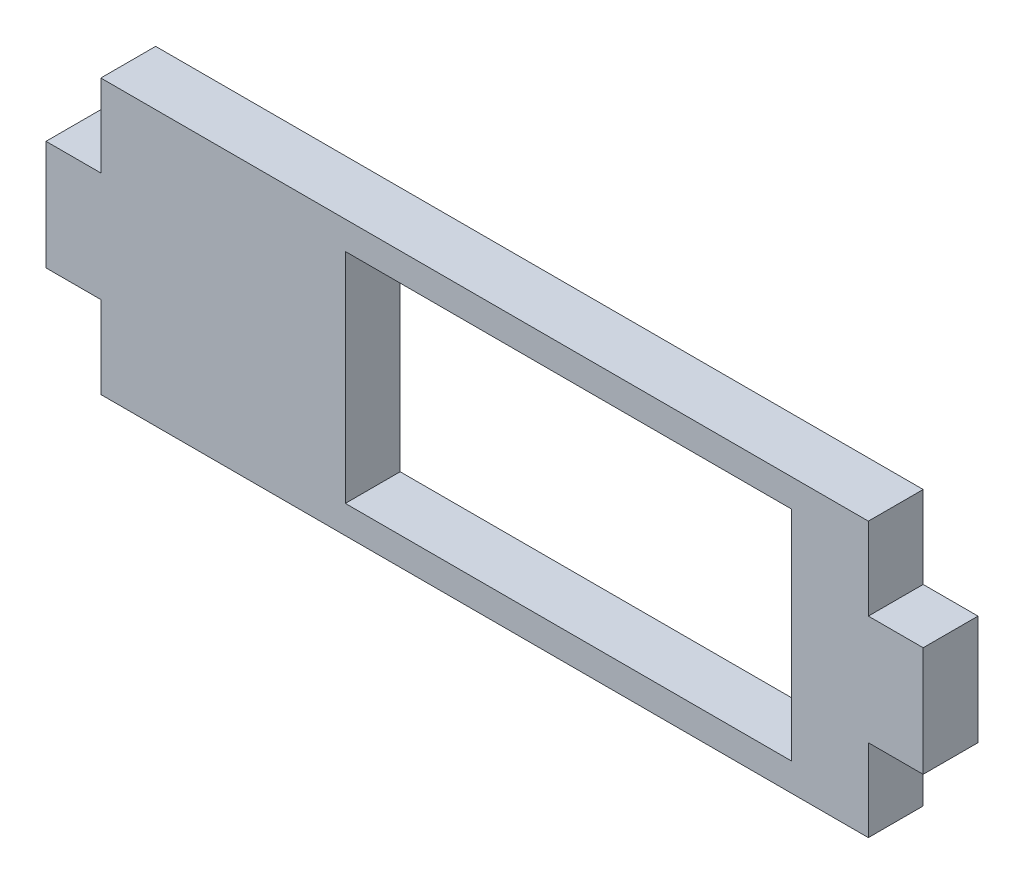
SolidWorks part; units mm, degrees
material "아크릴(내충격성)"
ref_plane "정면" through (0, 0, 0) normal (0, 0, 1) x (1, 0, 0)
ref_plane "윗면" through (0, 0, 0) normal (0, 1, 0) x (1, 0, 0)
ref_plane "우측면" through (0, 0, 0) normal (1, 0, 0) x (0, 0, -1)
sketch "스케치1" plane through (0, 0, 0) normal (0, 0, 1) x (1, 0, 0)
  line L0 (-40, 5) -> (-40, -5)
  line L5 (-35, 12.5) -> (35, 12.5)
  line L6 (-35, 12.5) -> (-35, 5)
  line L7 (-35, -12.5) -> (35, -12.5)
  line L8 (35, 12.5) -> (35, 5)
  line L9 (-35, 12.5) -> (35, -12.5) construction
  line L10 (-35, -12.5) -> (35, 12.5) construction
  line L11 (0, 0) -> (0, -6.3413)
  line L12 (-40, 5) -> (-35, 5)
  line L13 (40, -5) -> (35, -5)
  line L14 (-40, -5) -> (-35, -5)
  line L15 (40, 5) -> (40, -5)
  line L16 (40, 5) -> (35, 5)
  line L17 (-35, -5) -> (-35, -12.5)
  line L18 (35, -5) -> (35, -12.5)
  point P0 (0, 0)
  dimension "D1" = 70
  dimension "D2" = 25
extrude "보스-돌출1" add sketch "스케치1" along normal blind 5
sketch "스케치2" plane through (0, 0, 5) normal (0, 0, 1) x (1, 0, 0)
  line L6 (28, -9.95) -> (-12.7, -9.95)
  line L7 (-12.7, -9.95) -> (-12.7, 9.95)
  line L8 (-12.7, 9.95) -> (28, 9.95)
  line L9 (28, 9.95) -> (28, -9.95)
extrude "컷-돌출1" cut sketch "스케치2" against normal through all
